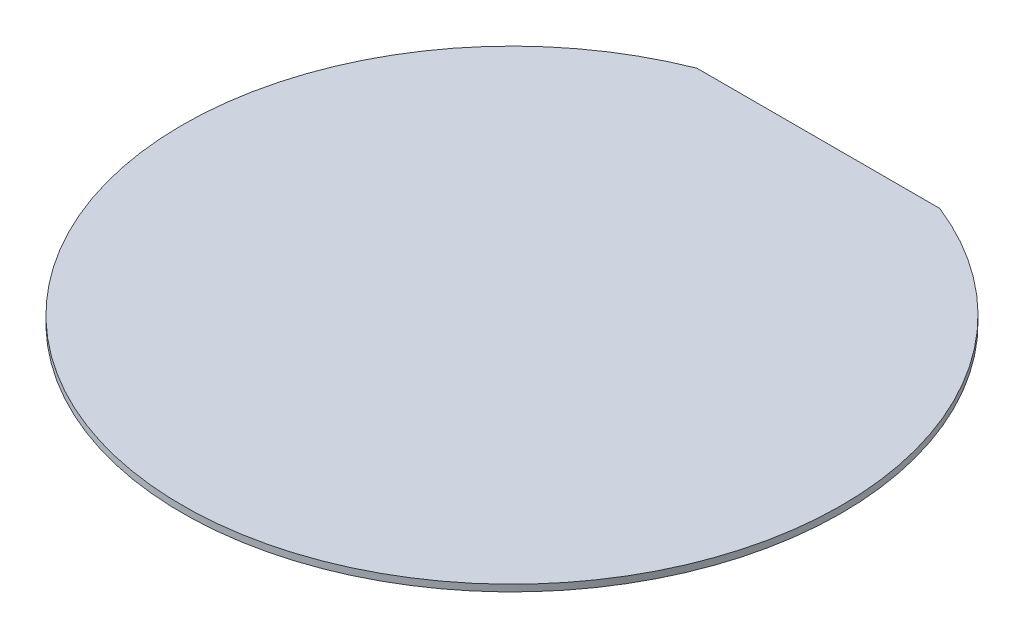
SolidWorks part; units mm, degrees
material "PC High Viscosity"
ref_plane "Front Plane" through (0, 0, 0) normal (0, 0, 1) x (1, 0, 0)
ref_plane "Top Plane" through (0, 0, 0) normal (0, 1, 0) x (1, 0, 0)
ref_plane "Right Plane" through (0, 0, 0) normal (1, 0, 0) x (0, 0, -1)
sketch "Sketch1" plane through (0, 0, 0) normal (0, 1, 0) x (1, 0, 0)
  line L0 (-6.5431, 16.5) -> (6.5431, 16.5)
  arc A0 (-6.5431, 16.5) -> (6.5431, 16.5) centre (0, 0) ccw
  dimension "D1" = 35.5
  dimension "D2" = 16.5
extrude "Boss-Extrude1" add sketch "Sketch1" along normal blind 0.36 contours A0 L0
